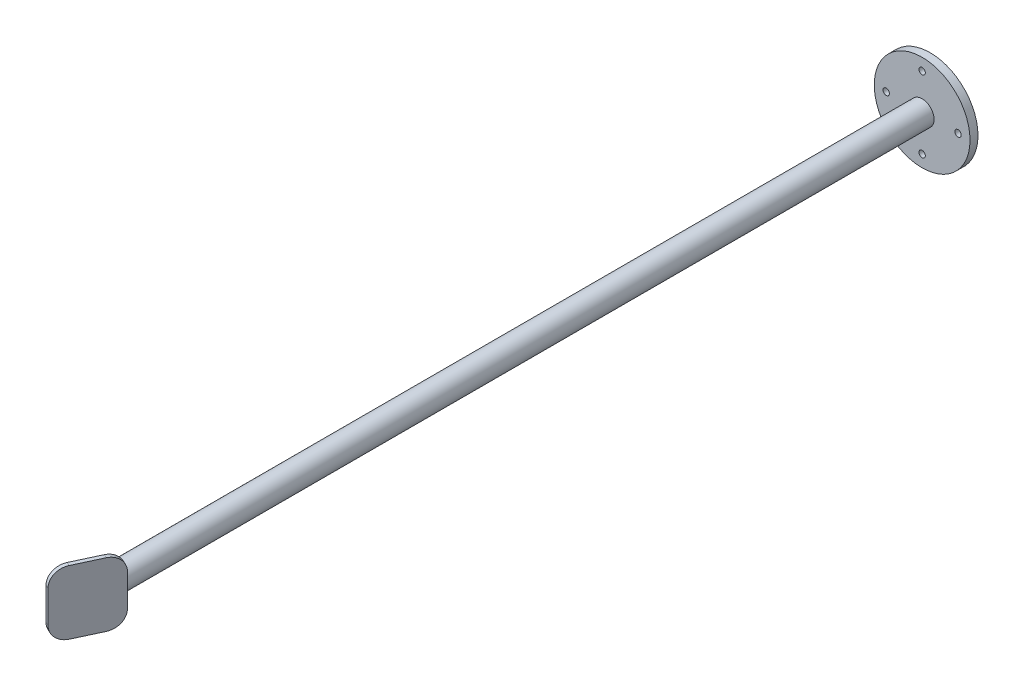
SolidWorks part; units mm, degrees
material "201 Annealed Stainless Steel (SS)"
ref_plane "Front Plane" through (0, 0, 0) normal (0, 0, 1) x (1, 0, 0)
ref_plane "Top Plane" through (0, 0, 0) normal (0, 1, 0) x (1, 0, 0)
ref_plane "Right Plane" through (0, 0, 0) normal (1, 0, 0) x (0, 0, -1)
sketch "Sketch1" plane through (0, 0, 0) normal (0, 0, 1) x (1, 0, 0)
  line L0 (0, 0) -> (0, 45) construction
  circle A0 centre (0, 0) radius 60
  circle A1 centre (0, 45) radius 4
  circle A2 centre (45, 0) radius 4
  circle A3 centre (0, -45) radius 4
  circle A4 centre (-45, 0) radius 4
  point P5 (0, 0)
  point P14 (0, 0)
  dimension "D1" = 120
  dimension "D2" = 8
  dimension "D3" = 45
  dimension "D4" = 4
extrude "Boss-Extrude1" add sketch "Sketch1" along normal blind 10
sketch "Sketch2" plane through (0, 0, 10) normal (0, 0, 1) x (1, 0, 0)
  circle A0 centre (0, 0) radius 15
  dimension "D1" = 30
extrude "Boss-Extrude2" add sketch "Sketch2" along normal blind 1080
sketch "Sketch3" plane through (0, 0, 1090) normal (0, 0, 1) x (1, 0, 0)
  line L0 (0, 0) -> (-15, 0) construction
  line L1 (-15, 19.3916) -> (-15, -19.3916)
  circle A0 centre (0, 0) radius 15 construction
  point P7 (-15, 0)
ref_plane "Plane1" through (405.1733, 0, 188.9354) normal (0.9063, 0, 0.4226) x (0, -1, 0)
sketch "Sketch4" plane through (405.1733, 0, 188.9354) normal (0.9063, 0, 0.4226) x (0, -1, 0)
  line L1 (15, -1062.8755) -> (-15, -1062.8755)
  line L2 (15, -1062.8755) -> (15, -912.8755)
  line L3 (15, -912.8755) -> (-15, -912.8755)
  line L4 (-15, -1062.8755) -> (-15, -912.8755)
  line L5 (15, -1062.8755) -> (-15, -912.8755) construction
  line L6 (15, -912.8755) -> (-15, -1062.8755) construction
  point P0 (0, -987.8755)
  point P5 (-3.8585, -943.5189)
  dimension "D1" = 30
  dimension "D2" = 150
extrude "Cut-Extrude1" cut sketch "Sketch4" along normal up to next contours L4 L3 L2 L1
sketch "Sketch5" plane through (405.1733, 0, 188.9354) normal (0.9063, 0, 0.4226) x (0.4226, 0, -0.9063)
  line L1 (-941.2217, -40) -> (-976.2217, -40)
  line L2 (-921.2217, -20) -> (-921.2217, 20)
  line L3 (-941.2217, 40) -> (-976.2217, 40)
  line L4 (-996.2217, -20) -> (-996.2217, 20)
  line L5 (-921.2217, -40) -> (-996.2217, 40) construction
  line L6 (-921.2217, 40) -> (-996.2217, -40) construction
  arc A0 (-976.2217, 40) -> (-996.2217, 20) centre (-976.2217, 20) ccw
  arc A1 (-921.2217, 20) -> (-941.2217, 40) centre (-941.2217, 20) ccw
  arc A2 (-941.2217, -40) -> (-921.2217, -20) centre (-941.2217, -20) ccw
  arc A3 (-976.2217, -40) -> (-996.2217, -20) centre (-976.2217, -20) cw
  point P0 (-958.7217, 0)
  point P17 (0, 0)
  dimension "D1" = 20
  dimension "D2" = 80
  dimension "D3" = 75
extrude "Boss-Extrude3" add sketch "Sketch5" along normal blind 5
